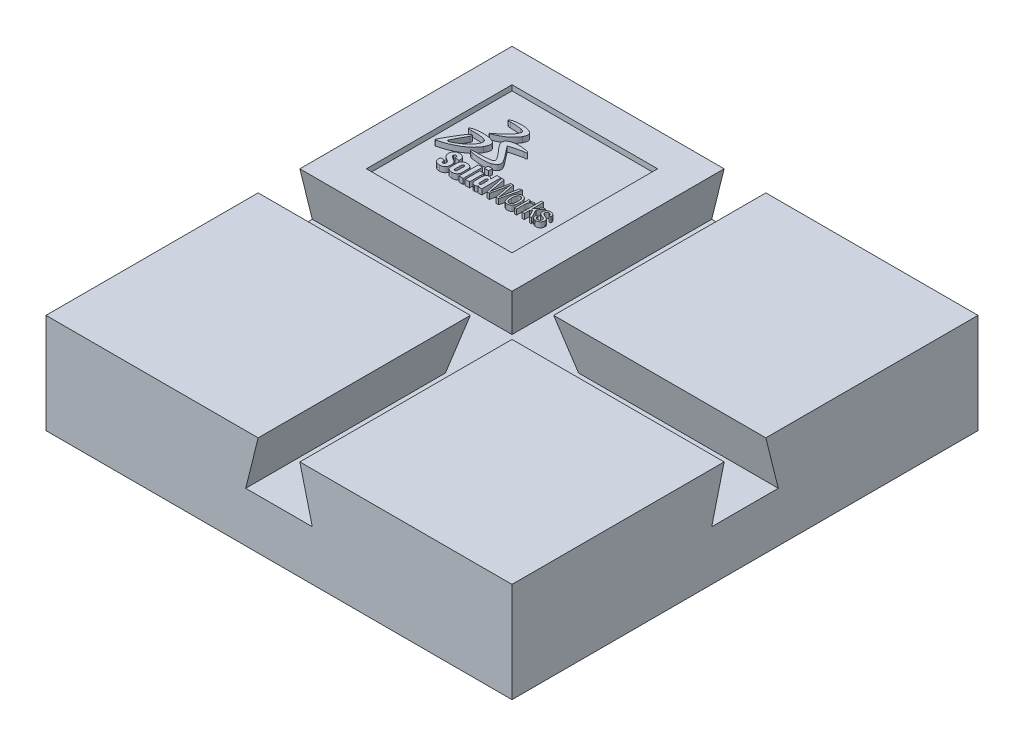
SolidWorks part; units mm, degrees
material "PW40:11:Ar:0:-1:Re:14:Ts:15:16:17:18:19:20:"
ref_plane "Front" through (0, 0, 0) normal (0, 0, 1) x (1, 0, 0)
ref_plane "Top" through (0, 0, 0) normal (0, 1, 0) x (1, 0, 0)
ref_plane "Right" through (0, 0, 0) normal (1, 0, 0) x (0, 0, -1)
sketch "Sketch1" plane through (0, 0, 0) normal (0, 1, 0) x (1, 0, 0)
  line L0 (-44.45, -44.45) -> (44.45, -44.45)
  line L1 (-44.45, -44.45) -> (-44.45, 44.45)
  line L2 (44.45, 44.45) -> (-44.45, 44.45)
  line L3 (44.45, 44.45) -> (44.45, -44.45)
  line L4 (-44.45, -44.45) -> (44.45, 44.45) construction
  dimension "D1" = 88.9
extrude "Base-Extrude" add sketch "Sketch1" along normal blind 19.05
sketch "Sketch2" plane through (0, 0, 44.45) normal (0, 0, 1) x (1, 0, 0)
  line L0 (0, -6.2714) -> (0, 26.7115) construction
  line L1 (6.35, 9.525) -> (-6.35, 9.525)
  line L2 (-6.35, 9.525) -> (-3.9752, 19.05)
  line L3 (-44.45, 19.05) -> (44.45, 19.05) construction
  line L4 (6.35, 9.525) -> (3.9752, 19.05)
  line L5 (-3.9752, 19.05) -> (3.9752, 19.05)
  point P6 (0, 9.525)
  point P11 (0, 19.05)
  dimension "D1" = 28
  dimension "D2" = 9.525
  dimension "D3" = 12.7
extrude "Cut-Extrude1" cut sketch "Sketch2" against normal through all
sketch "Sketch3" plane through (44.45, -3.5382, -0.6646) normal (1, 0, 0) x (0, 0, -1)
  line L0 (-0.6646, -6.2714) -> (-0.6646, 26.7115) construction
  line L1 (5.6854, 13.0632) -> (-7.0146, 13.0632)
  line L2 (-7.0146, 13.0632) -> (-4.6397, 22.5882)
  line L3 (43.7854, 22.5882) -> (-45.1146, 22.5882) construction
  line L4 (5.6854, 13.0632) -> (3.3106, 22.5882)
  line L5 (-4.6397, 22.5882) -> (3.3106, 22.5882)
  point P6 (-0.6646, 13.0632)
  point P11 (-0.6646, 22.5882)
  dimension "D1" = 28
  dimension "D2" = 9.525
  dimension "D3" = 12.7
extrude "Cut-Extrude2" cut sketch "Sketch3" against normal through all
sketch "Sketch8" plane through (0, 19.05, 0) normal (0, 1, 0) x (-1, 0, 0)
  line L8 (38.1, -10.3252) -> (10.3252, -10.3252)
  line L9 (10.3252, -10.3252) -> (10.3252, -38.1)
  line L10 (10.3252, -38.1) -> (38.1, -38.1)
  line L11 (38.1, -38.1) -> (38.1, -10.3252)
  line L12 (38.1, -10.3252) -> (10.3252, -10.3252)
  line L13 (10.3252, -10.3252) -> (10.3252, -38.1)
  line L14 (10.3252, -38.1) -> (38.1, -38.1)
  line L15 (38.1, -38.1) -> (38.1, -10.3252)
  dimension "D1" = 6.35
extrude "Cut-Extrude4" cut sketch "Sketch8" against normal blind 1.016
sketch "Sketch7" plane through (-67.0126, 18.034, 30.4205) normal (0, 1, 0) x (1, 0, 0)
  line L0 (51.3496, 49.9707) -> (52.2912, 51.1693)
  line L1 (38.9273, 52.0869) -> (39.735, 52.0869)
  line L2 (38.9273, 52.0869) -> (38.9273, 48.3974)
  line L3 (38.9273, 48.3974) -> (39.735, 48.3974)
  line L4 (39.735, 52.0869) -> (39.735, 48.3974)
  line L5 (40.076, 51.2067) -> (40.9016, 51.2067)
  line L6 (40.076, 51.2067) -> (40.076, 48.4299)
  line L7 (40.076, 48.4299) -> (40.9016, 48.4299)
  line L8 (40.9016, 51.2067) -> (40.9016, 48.4299)
  line L9 (40.076, 52.7853) -> (40.9016, 52.7853)
  line L10 (40.076, 52.7853) -> (40.076, 52.0869)
  line L11 (40.076, 52.0869) -> (40.9016, 52.0869)
  line L12 (40.9016, 52.7853) -> (40.9016, 52.0869)
  line L13 (50.9296, 52.0869) -> (51.3496, 52.0869)
  line L14 (50.9296, 52.0869) -> (50.9296, 48.4299)
  line L15 (50.9296, 48.4299) -> (51.3496, 48.4299)
  line L16 (51.3496, 52.0869) -> (51.3496, 49.9707)
  line L17 (52.2912, 51.1693) -> (52.7014, 51.1693)
  line L18 (52.7014, 51.1693) -> (51.8776, 50.1206)
  line L19 (51.8776, 50.1206) -> (52.7638, 48.4312)
  line L20 (52.7638, 48.4312) -> (52.3206, 48.4312)
  line L21 (52.3206, 48.4312) -> (51.6119, 49.7824)
  line L22 (51.6119, 49.7824) -> (51.3496, 49.4485)
  line L23 (51.3496, 49.4485) -> (51.3496, 48.4299)
  spline S0 degree 3 poles (34.8747, 62.6315) (34.701, 62.5806) (34.3504, 62.4842) (34.3801, 62.3564) knots 0 0 0 0 1 1 1 1
  spline S1 degree 3 poles (34.3801, 62.3564) (34.3989, 62.2743) (34.4687, 62.2353) (34.8756, 62.2357) knots 0 0 0 0 1 1 1 1
  spline S2 degree 3 poles (34.8756, 62.2357) (35.7863, 62.2368) (36.4942, 62.1777) (36.9788, 62.0908) knots 0 0 0 0 1 1 1 1
  spline S3 degree 3 poles (36.9788, 62.0908) (37.9649, 61.9128) (37.7327, 61.4152) (37.4525, 60.9389) knots 0 0 0 0 1 1 1 1
  spline S4 degree 3 poles (37.4525, 60.9389) (36.7725, 59.7797) (34.9361, 58.4753) (34.8296, 58.4018) knots 0 0 0 0 1 1 1 1
  spline S5 degree 3 poles (34.8296, 58.4018) (34.6896, 58.3053) (34.7661, 58.249) (34.8885, 58.2946) knots 0 0 0 0 1 1 1 1
  spline S6 degree 3 poles (34.8885, 58.2946) (36.3776, 58.8484) (37.8779, 59.8035) (38.4839, 60.9637) knots 0 0 0 0 1 1 1 1
  spline S7 degree 3 poles (38.4839, 60.9637) (38.998, 61.9477) (38.6295, 62.4147) (37.8459, 62.6346) knots 0 0 0 0 1 1 1 1
  spline S8 degree 3 poles (37.8459, 62.6346) (36.4473, 63.0282) (34.9969, 62.6676) (34.8747, 62.6315) knots 0 0 0 0 1 1 1 1
  spline S9 degree 3 poles (37.6876, 58.6602) (36.9077, 57.9859) (38.0644, 56.875) (38.6082, 56.2381) knots 0 0 0 0 1 1 1 1
  spline S10 degree 3 poles (38.6082, 56.2381) (39.1375, 55.619) (39.778, 54.8332) (39.8081, 54.5633) knots 0 0 0 0 1 1 1 1
  spline S11 degree 3 poles (39.8081, 54.5633) (39.8216, 54.4396) (39.797, 54.2989) (39.6488, 54.2071) knots 0 0 0 0 1 1 1 1
  spline S12 degree 3 poles (39.6488, 54.2071) (39.4065, 54.0557) (38.4064, 53.9096) (36.3378, 53.9115) knots 0 0 0 0 1 1 1 1
  spline S13 degree 3 poles (36.3378, 53.9115) (35.889, 53.9119) (35.7975, 53.868) (35.7859, 53.7876) knots 0 0 0 0 1 1 1 1
  spline S14 degree 3 poles (35.7859, 53.7876) (35.7796, 53.7454) (35.7658, 53.648) (36.3368, 53.5045) knots 0 0 0 0 1 1 1 1
  spline S15 degree 3 poles (36.3368, 53.5045) (36.3523, 53.5002) (38.7076, 53.0672) (39.9638, 53.5045) knots 0 0 0 0 1 1 1 1
  spline S16 degree 3 poles (39.9638, 53.5045) (41.2469, 53.9423) (40.9241, 54.6815) (40.6938, 55.1084) knots 0 0 0 0 1 1 1 1
  spline S17 degree 3 poles (40.6938, 55.1084) (40.3394, 55.7661) (38.704, 57.6782) (38.5691, 57.9382) knots 0 0 0 0 1 1 1 1
  spline S18 degree 3 poles (41.0808, 58.5984) (41.5303, 58.5949) (41.6236, 58.6418) (41.634, 58.7227) knots 0 0 0 0 1 1 1 1
  spline S19 degree 3 poles (41.634, 58.7227) (41.6429, 58.7897) (41.5146, 58.9351) (41.0872, 59.0266) knots 0 0 0 0 1 1 1 1
  spline S20 degree 3 poles (41.0872, 59.0266) (40.6842, 59.1132) (38.6231, 59.4689) (37.6876, 58.6602) knots 0 0 0 0 1 1 1 1
  spline S21 degree 3 poles (35.7639, 57.5374) (34.3125, 57.9667) (32.7304, 57.5937) (32.489, 57.5297) knots 0 0 0 0 1 1 1 1
  spline S22 degree 3 poles (32.489, 57.5297) (32.1238, 57.4329) (31.9096, 57.3353) (31.9245, 57.2208) knots 0 0 0 0 1 1 1 1
  spline S23 degree 3 poles (31.9245, 57.2208) (31.936, 57.1362) (32.0293, 57.078) (32.4784, 57.089) knots 0 0 0 0 1 1 1 1
  spline S24 degree 3 poles (32.4784, 57.089) (33.5485, 57.115) (34.4354, 57.0789) (34.9957, 56.9219) knots 0 0 0 0 1 1 1 1
  spline S25 degree 3 poles (34.9957, 56.9219) (35.6899, 56.7282) (35.7752, 56.3707) (35.4317, 55.6683) knots 0 0 0 0 1 1 1 1
  spline S26 degree 3 poles (35.4317, 55.6683) (35.2727, 55.3437) (35.0376, 55.0081) (34.6815, 54.6517) knots 0 0 0 0 1 1 1 1
  spline S27 degree 3 poles (34.6815, 54.6517) (33.9709, 53.9388) (33.0828, 53.4745) (32.5824, 53.2213) knots 0 0 0 0 1 1 1 1
  spline S28 degree 3 poles (32.5824, 53.2213) (32.0958, 52.9744) (31.9179, 53.1055) (31.972, 53.3491) knots 0 0 0 0 1 1 1 1
  spline S29 degree 3 poles (33.4188, 56.0359) (33.5225, 56.2172) (33.5408, 56.3877) (33.4188, 56.4387) knots 0 0 0 0 1 1 1 1
  spline S30 degree 3 poles (33.4188, 56.4387) (33.3141, 56.4831) (33.1244, 56.3361) (32.9273, 56.1081) knots 0 0 0 0 1 1 1 1
  spline S31 degree 3 poles (32.9273, 56.1081) (32.1217, 55.1725) (30.6359, 52.3258) (30.6085, 52.2323) knots 0 0 0 0 1 1 1 1
  spline S32 degree 3 poles (30.6085, 52.2323) (30.5811, 52.1427) (30.651, 52.1316) (30.6778, 52.1311) knots 0 0 0 0 1 1 1 1
  spline S33 degree 3 poles (30.6778, 52.1311) (31.3068, 52.1357) (35.1687, 53.278) (36.4149, 55.6125) knots 0 0 0 0 1 1 1 1
  spline S34 degree 3 poles (36.4149, 55.6125) (37.071, 56.8419) (36.739, 57.2487) (35.7639, 57.5374) knots 0 0 0 0 1 1 1 1
  spline S35 degree 3 poles (31.972, 53.3491) (31.9763, 53.3688) (33.3683, 55.9476) (33.4188, 56.0359) knots 0 0 0 0 1 1 1 1
  spline S36 degree 3 poles (41.0808, 58.5984) (40.938, 58.5996) (38.5354, 58.003) (38.5691, 57.9382) knots 0 0 0 0 1 1 1 1
  spline S37 degree 3 poles (54.0476, 50.414) (54.0628, 50.7362) (53.9469, 50.8873) (53.6184, 50.8873) knots 0 0 0 0 1 1 1 1
  spline S38 degree 3 poles (53.6184, 50.8873) (53.3455, 50.8873) (53.1896, 50.7598) (53.1896, 50.4772) knots 0 0 0 0 1 1 1 1
  spline S39 degree 3 poles (53.1896, 50.4772) (53.1896, 50.127) (53.4774, 50.0822) (53.7416, 49.9707) knots 0 0 0 0 1 1 1 1
  spline S40 degree 3 poles (53.7416, 49.9707) (54.1306, 49.794) (54.5215, 49.6973) (54.5215, 49.19) knots 0 0 0 0 1 1 1 1
  spline S41 degree 3 poles (54.5215, 49.19) (54.5215, 48.6727) (54.1604, 48.3504) (53.6035, 48.3558) knots 0 0 0 0 1 1 1 1
  spline S42 degree 3 poles (53.6035, 48.3558) (53.3648, 48.3504) (53.0729, 48.4336) (52.9308, 48.6385) knots 0 0 0 0 1 1 1 1
  spline S43 degree 3 poles (52.9308, 48.6385) (52.7702, 48.8529) (52.7794, 49.0336) (52.7794, 49.219) knots 0 0 0 0 1 1 1 1
  spline S44 degree 1 poles (52.7794, 49.219) (53.1462, 49.219) knots 0 0 2.6406 2.6406
  spline S45 degree 3 poles (53.1462, 49.219) (53.1318, 48.8873) (53.2435, 48.6822) (53.6035, 48.6822) knots 0 0 0 0 1 1 1 1
  spline S46 degree 3 poles (53.6035, 48.6822) (53.9174, 48.6822) (54.1216, 48.8094) (54.1216, 49.1409) knots 0 0 0 0 1 1 1 1
  spline S47 degree 3 poles (54.1216, 49.1409) (54.1216, 49.5261) (53.7313, 49.5605) (53.4532, 49.678) knots 0 0 0 0 1 1 1 1
  spline S48 degree 3 poles (53.4532, 49.678) (53.0339, 49.8334) (52.7897, 49.975) (52.7897, 50.4476) knots 0 0 0 0 1 1 1 1
  spline S49 degree 3 poles (52.7897, 50.4476) (52.7897, 50.9172) (53.1169, 51.2146) (53.5851, 51.2146) knots 0 0 0 0 1 1 1 1
  spline S50 degree 3 poles (53.5851, 51.2146) (54.1216, 51.2146) (54.4336, 50.9695) (54.4236, 50.414) knots 0 0 0 0 1 1 1 1
  spline S51 degree 1 poles (54.4236, 50.414) (54.0476, 50.414) knots 0 0 2.707 2.707
  spline S54 degree 1 poles (49.8695, 50.6977) (49.8796, 50.6977) knots 0 0 0.0723 0.0723
  spline S55 degree 3 poles (49.8796, 50.6977) (50.0399, 51.0533) (50.2699, 51.2044) (50.6736, 51.1693) knots 0 0 0 0 1 1 1 1
  spline S56 degree 1 poles (50.6736, 51.1693) (50.6736, 50.7895) knots 0 0 2.7343 2.7343
  spline S57 degree 3 poles (50.6736, 50.7895) (50.1763, 50.8776) (49.8834, 50.5656) (49.8834, 50.0732) knots 0 0 0 0 1 1 1 1
  spline S58 degree 1 poles (49.8834, 50.0732) (49.8834, 48.4299) knots 0 0 11.832 11.832
  spline S59 degree 1 poles (49.8834, 48.4299) (49.4982, 48.4299) knots 0 0 2.7735 2.7735
  spline S60 degree 1 poles (49.4982, 48.4299) (49.4982, 51.1407) knots 0 0 19.5176 19.5176
  spline S61 degree 1 poles (49.4982, 51.1407) (49.8695, 51.1407) knots 0 0 2.6738 2.6738
  spline S62 degree 1 poles (49.8695, 51.1407) (49.8695, 50.6977) knots 0 0 3.1895 3.1895
  spline S63 degree 3 poles (48.1689, 50.8873) (47.7751, 50.8873) (47.5985, 50.5759) (47.5985, 49.7553) knots 0 0 0 0 1 1 1 1
  spline S64 degree 3 poles (47.5985, 49.7553) (47.5985, 49.1165) (47.7208, 48.6822) (48.1689, 48.6822) knots 0 0 0 0 1 1 1 1
  spline S65 degree 3 poles (48.1689, 48.6822) (48.6271, 48.6822) (48.7394, 49.1165) (48.7394, 49.7553) knots 0 0 0 0 1 1 1 1
  spline S66 degree 3 poles (48.7394, 49.7553) (48.7394, 50.5759) (48.5745, 50.8873) (48.1689, 50.8873) knots 0 0 0 0 1 1 1 1
  spline S67 degree 3 poles (48.1689, 48.3558) (47.5841, 48.3558) (47.1992, 48.7071) (47.1992, 49.8774) knots 0 0 0 0 1 1 1 1
  spline S68 degree 3 poles (47.1992, 49.8774) (47.1992, 50.6977) (47.5008, 51.2146) (48.1689, 51.2146) knots 0 0 0 0 1 1 1 1
  spline S69 degree 3 poles (48.1689, 51.2146) (48.8376, 51.2146) (49.1406, 50.6977) (49.1406, 49.8774) knots 0 0 0 0 1 1 1 1
  spline S70 degree 3 poles (49.1406, 49.8774) (49.1406, 48.7028) (48.7644, 48.3558) (48.1689, 48.3558) knots 0 0 0 0 1 1 1 1
  spline S71 degree 1 poles (44.6954, 48.4299) (44.1923, 48.4299) knots 0 0 3.622 3.622
  spline S72 degree 1 poles (44.1923, 48.4299) (43.4125, 52.0869) knots 0 0 26.922008 26.922008
  spline S73 degree 1 poles (43.4125, 52.0869) (43.8615, 52.0869) knots 0 0 3.2324 3.2324
  spline S74 degree 1 poles (43.8615, 52.0869) (44.3383, 49.5652) knots 0 0 18.477951 18.477951
  spline S75 degree 3 poles (44.3383, 49.5652) (44.3826, 49.3169) (44.417, 49.063) (44.4467, 48.7218) knots 0 0 0 0 1 1 1 1
  spline S76 degree 1 poles (44.4467, 48.7218) (44.4561, 48.7218) knots 0 0 0.0674 0.0674
  spline S77 degree 3 poles (44.4561, 48.7218) (44.4902, 49.0042) (44.5193, 49.2725) (44.5734, 49.5361) knots 0 0 0 0 1 1 1 1
  spline S78 degree 1 poles (44.5734, 49.5361) (45.1099, 52.0869) knots 0 0 18.766937 18.766937
  spline S79 degree 1 poles (45.1099, 52.0869) (45.6114, 52.0869) knots 0 0 3.6113 3.6113
  spline S80 degree 1 poles (45.6114, 52.0869) (46.0959, 49.5652) knots 0 0 18.48836 18.48836
  spline S81 degree 3 poles (46.0959, 49.5652) (46.138, 49.3213) (46.1673, 49.0778) (46.2017, 48.7218) knots 0 0 0 0 1 1 1 1
  spline S82 degree 1 poles (46.2017, 48.7218) (46.212, 48.7218) knots 0 0 0.0743 0.0743
  spline S83 degree 3 poles (46.212, 48.7218) (46.2457, 49.0042) (46.275, 49.2725) (46.3292, 49.5361) knots 0 0 0 0 1 1 1 1
  spline S84 degree 1 poles (46.3292, 49.5361) (46.8601, 52.0869) knots 0 0 18.758746 18.758746
  spline S85 degree 1 poles (46.8601, 52.0869) (47.3098, 52.0869) knots 0 0 3.2383 3.2383
  spline S86 degree 1 poles (47.3098, 52.0869) (46.4513, 48.4299) knots 0 0 27.046027 27.046027
  spline S87 degree 1 poles (46.4513, 48.4299) (45.9492, 48.4299) knots 0 0 3.6152 3.6152
  spline S88 degree 1 poles (45.9492, 48.4299) (45.4614, 50.9117) knots 0 0 18.210995 18.210995
  spline S89 degree 3 poles (45.4614, 50.9117) (45.413, 51.1508) (45.3841, 51.3943) (45.3537, 51.7944) knots 0 0 0 0 1 1 1 1
  spline S90 degree 1 poles (45.3537, 51.7944) (45.3436, 51.7944) knots 0 0 0.0733 0.0733
  spline S91 degree 3 poles (45.3436, 51.7944) (45.3103, 51.4429) (45.2806, 51.1759) (45.2271, 50.9117) knots 0 0 0 0 1 1 1 1
  spline S92 degree 1 poles (45.2271, 50.9117) (44.6954, 48.4299) knots 0 0 18.274666 18.274666
  spline S93 degree 3 poles (41.998, 49.4145) (41.998, 49.2531) (41.998, 48.9754) (42.2217, 48.9754) knots 0 0 0 0 1 1 1 1
  spline S94 degree 3 poles (42.2217, 48.9754) (42.4312, 48.9754) (42.4608, 49.1846) (42.4608, 49.4488) knots 0 0 0 0 1 1 1 1
  spline S95 degree 1 poles (42.4608, 49.4488) (42.4608, 50.0925) knots 0 0 4.6347 4.6347
  spline S96 degree 3 poles (42.4608, 50.0925) (42.4608, 50.3266) (42.4262, 50.6095) (42.236, 50.6038) knots 0 0 0 0 1 1 1 1
  spline S97 degree 3 poles (42.236, 50.6038) (41.9883, 50.6038) (41.998, 50.2965) (41.998, 50.1211) knots 0 0 0 0 1 1 1 1
  spline S98 degree 1 poles (41.998, 50.1211) (41.998, 49.4145) knots 0 0 5.0879 5.0879
  spline S99 degree 1 poles (42.5147, 48.4299) (42.5147, 48.7461) knots 0 0 2.2764 2.2764
  spline S100 degree 1 poles (42.5147, 48.7461) (42.5054, 48.7461) knots 0 0 0.0664 0.0664
  spline S101 degree 3 poles (42.5054, 48.7461) (42.3631, 48.4821) (42.1293, 48.3412) (41.9006, 48.3412) knots 0 0 0 0 1 1 1 1
  spline S102 degree 3 poles (41.9006, 48.3412) (41.3346, 48.3607) (41.2219, 48.8921) (41.2219, 49.356) knots 0 0 0 0 1 1 1 1
  spline S103 degree 1 poles (41.2219, 49.356) (41.2219, 50.3017) knots 0 0 6.8086 6.8086
  spline S104 degree 3 poles (41.2219, 50.3017) (41.2219, 50.7312) (41.3732, 51.2386) (41.8859, 51.2386) knots 0 0 0 0 1 1 1 1
  spline S105 degree 3 poles (41.8859, 51.2386) (42.0914, 51.2386) (42.2901, 51.1508) (42.4504, 50.9117) knots 0 0 0 0 1 1 1 1
  spline S106 degree 1 poles (42.4504, 50.9117) (42.4608, 50.9117) knots 0 0 0.0747 0.0747
  spline S107 degree 1 poles (42.4608, 50.9117) (42.4608, 52.0869) knots 0 0 8.4609 8.4609
  spline S108 degree 1 poles (42.4608, 52.0869) (43.2368, 52.0869) knots 0 0 5.5869 5.5869
  spline S109 degree 1 poles (43.2368, 52.0869) (43.2368, 48.4299) knots 0 0 26.3301 26.3301
  spline S110 degree 1 poles (43.2368, 48.4299) (42.5147, 48.4299) knots 0 0 5.1992 5.1992
  spline S117 degree 3 poles (37.3865, 49.1409) (37.4004, 48.9847) (37.4645, 48.9019) (37.6244, 48.9019) knots 0 0 0 0 1 1 1 1
  spline S118 degree 3 poles (37.6244, 48.9019) (37.7858, 48.9019) (37.8487, 48.9847) (37.8637, 49.1409) knots 0 0 0 0 1 1 1 1
  spline S119 degree 1 poles (37.8637, 49.1409) (37.8637, 50.3611) knots 0 0 8.7851 8.7851
  spline S120 degree 3 poles (37.8637, 50.3611) (37.8637, 50.5357) (37.8053, 50.6779) (37.6244, 50.6779) knots 0 0 0 0 1 1 1 1
  spline S121 degree 3 poles (37.6244, 50.6779) (37.4441, 50.6779) (37.3865, 50.5357) (37.3865, 50.3611) knots 0 0 0 0 1 1 1 1
  spline S122 degree 1 poles (37.3865, 50.3611) (37.3865, 49.1409) knots 0 0 8.7851 8.7851
  spline S123 degree 3 poles (36.6102, 50.3017) (36.6102, 51.0046) (37.0252, 51.2386) (37.6244, 51.2386) knots 0 0 0 0 1 1 1 1
  spline S124 degree 3 poles (37.6244, 51.2386) (38.3079, 51.2386) (38.6391, 50.9172) (38.6391, 50.3017) knots 0 0 0 0 1 1 1 1
  spline S125 degree 1 poles (38.6391, 50.3017) (38.6391, 49.19) knots 0 0 8.0039 8.0039
  spline S126 degree 3 poles (38.6391, 49.19) (38.5997, 48.5704) (38.2149, 48.3412) (37.6244, 48.3412) knots 0 0 0 0 1 1 1 1
  spline S127 degree 3 poles (37.6244, 48.3412) (37.0685, 48.3412) (36.6102, 48.5653) (36.6102, 49.19) knots 0 0 0 0 1 1 1 1
  spline S128 degree 1 poles (36.6102, 49.19) (36.6102, 50.3017) knots 0 0 8.0039 8.0039
  spline S129 degree 1 poles (34.9394, 49.6535) (34.9394, 49.3944) knots 0 0 1.8653 1.8653
  spline S130 degree 3 poles (34.9394, 49.3944) (34.9394, 49.1846) (35.0085, 48.9992) (35.281, 48.9992) knots 0 0 0 0 1 1 1 1
  spline S131 degree 3 poles (35.281, 48.9992) (35.4811, 48.9992) (35.5688, 49.1797) (35.5688, 49.3654) knots 0 0 0 0 1 1 1 1
  spline S132 degree 3 poles (35.5688, 49.3654) (35.5688, 49.6726) (35.3153, 49.7892) (35.0913, 49.9263) knots 0 0 0 0 1 1 1 1
  spline S133 degree 3 poles (35.0913, 49.9263) (34.827, 50.0774) (34.6033, 50.2189) (34.4429, 50.4039) knots 0 0 0 0 1 1 1 1
  spline S134 degree 3 poles (34.4429, 50.4039) (34.2856, 50.5903) (34.1929, 50.8142) (34.1929, 51.1366) knots 0 0 0 0 1 1 1 1
  spline S135 degree 3 poles (34.1929, 51.1366) (34.1929, 51.8237) (34.6076, 52.1754) (35.271, 52.1754) knots 0 0 0 0 1 1 1 1
  spline S136 degree 3 poles (35.271, 52.1754) (36.0184, 52.1754) (36.3987, 51.6778) (36.3589, 50.9904) knots 0 0 0 0 1 1 1 1
  spline S137 degree 1 poles (36.3589, 50.9904) (35.5688, 50.9904) knots 0 0 5.689 5.689
  spline S138 degree 3 poles (35.5688, 50.9904) (35.5587, 51.2044) (35.5688, 51.4973) (35.2856, 51.5167) knots 0 0 0 0 1 1 1 1
  spline S139 degree 3 poles (35.2856, 51.5167) (35.1105, 51.5313) (35.0085, 51.4331) (34.9885, 51.2732) knots 0 0 0 0 1 1 1 1
  spline S140 degree 3 poles (34.9885, 51.2732) (34.9637, 51.0533) (35.0766, 50.941) (35.2469, 50.8242) knots 0 0 0 0 1 1 1 1
  spline S141 degree 3 poles (35.2469, 50.8242) (35.5688, 50.6188) (35.8466, 50.4921) (36.0474, 50.3073) knots 0 0 0 0 1 1 1 1
  spline S142 degree 3 poles (36.0474, 50.3073) (36.2468, 50.1211) (36.364, 49.8774) (36.364, 49.4335) knots 0 0 0 0 1 1 1 1
  spline S143 degree 3 poles (36.364, 49.4335) (36.364, 48.7314) (35.9737, 48.3412) (35.2617, 48.3412) knots 0 0 0 0 1 1 1 1
  spline S144 degree 3 poles (35.2617, 48.3412) (34.4757, 48.3412) (34.145, 48.7797) (34.145, 49.2627) knots 0 0 0 0 1 1 1 1
  spline S145 degree 1 poles (34.145, 49.2627) (34.145, 49.6535) knots 0 0 2.8135 2.8135
  spline S146 degree 1 poles (34.145, 49.6535) (34.9394, 49.6535) knots 0 0 5.7197 5.7197
extrude "Extrude1" add sketch "Sketch7" along normal blind 1.016
